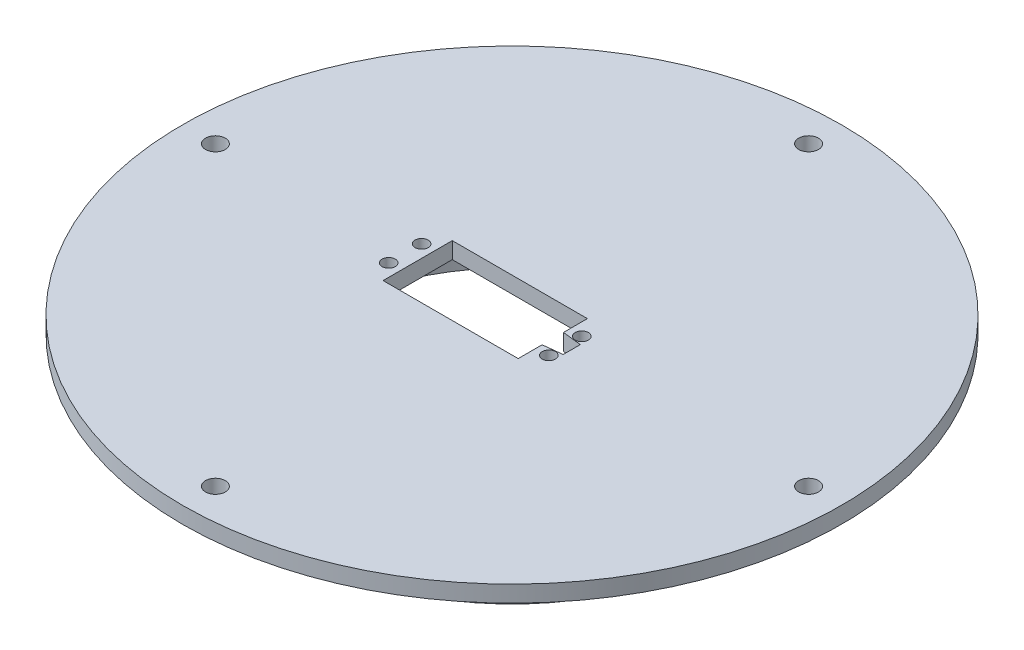
SolidWorks part; units mm, degrees
ref_plane "前视基准面" through (0, 0, 0) normal (0, 0, 1) x (1, 0, 0)
ref_plane "上视基准面" through (0, 0, 0) normal (0, 1, 0) x (1, 0, 0)
ref_plane "右视基准面" through (0, 0, 0) normal (1, 0, 0) x (0, 0, -1)
other "Configuration Table"
sketch "草图1" plane through (0, 0, 0) normal (0, 1, 0) x (1, 0, 0)
  line L0 (0, 0) -> (83.2464, 0) construction
  line L2 (-36.85, 10) -> (-36.85, -10) construction
  line L4 (17.15, 10) -> (17.15, -10) construction
  line L5 (-8.123, 10.2) -> (-8.123, -9.8) construction
  line L7 (-28.623, 10.5) -> (-28.623, -10.5)
  line L8 (-28.623, 10.5) -> (12.377, 10.5)
  line L9 (-28.623, -10.5) -> (12.377, -10.5)
  line L10 (12.377, 10.5) -> (12.377, -10.5)
  circle A0 centre (0, 0) radius 100
  dimension "D1" = 54
  dimension "D4" = 41
  dimension "D8" = 200
  dimension "D2" = 20
  dimension "D3" = 17.15
  dimension "D5" = 10.5
sketch "草图2" plane through (0, 0, 0) normal (0, 1, 0) x (1, 0, 0)
  line L2 (12.377, 10.5) -> (12.377, -10.5) construction
  line L4 (-28.623, 10.5) -> (-28.623, -10.5) construction
  line L5 (12.377, -10.5) -> (-28.623, -10.5)
  line L6 (-8.123, 10.5) -> (-8.123, -10.5) construction
  line L7 (12.377, 10.5) -> (12.377, -10.5)
  line L8 (-28.623, 10.5) -> (12.377, 10.5)
  line L9 (-28.623, 10.5) -> (-28.623, -10.5)
  line L10 (-28.623, 0) -> (12.377, 0) construction
  circle A0 centre (16.177, 5) radius 2
  circle A1 centre (16.177, -5) radius 2
  circle A2 centre (-32.423, -5) radius 2
  circle A3 centre (-32.423, 5) radius 2
  dimension "D2" = 10
  dimension "D1" = 10.5
  dimension "D3" = 48.6
extrude "凸台-拉伸1" add sketch "草图1" along normal blind 5 contours A0
sketch "草图3" plane through (0, 0, 0) normal (0, -1, 0) x (1, 0, 0)
  line L0 (0, 0) -> (0, 109.0175) construction
  circle A0 centre (0, 0) radius 90 construction
  circle A1 centre (0, 90) radius 3
  circle A2 centre (90, 0) radius 3
  circle A3 centre (0, -90) radius 3
  circle A4 centre (-90, 0) radius 3
  dimension "D1" = 4
extrude "切除-拉伸1" cut sketch "草图3" against normal through all
extrude "切除-拉伸3" cut sketch "草图2" along normal blind 10
sketch "草图4" plane through (0, 0, 0) normal (0, -1, 0) x (1, 0, 0)
  circle A0 centre (0, 0) radius 60
  circle A1 centre (0, 0) radius 65
extrude "凸台-拉伸2" add sketch "草图4" along normal blind 25
sketch "草图5" plane through (0, 5, 0) normal (0, 1, 0) x (1, 0, 0)
  line L0 (-28.623, 0) -> (12.377, 0) construction
  line L1 (-28.623, -10.5) -> (-28.623, 10.5) construction
  line L2 (12.377, 10.5) -> (12.377, -10.5) construction
  line L5 (12.377, -3.25) -> (12.377, 3.25)
  line L7 (12.377, 3.25) -> (18.1292, 2.6)
  line L8 (18.1292, 2.6) -> (18.1292, -2.6)
  line L9 (18.1292, 0) -> (12.377, 0)
  line L10 (12.377, -3.25) -> (18.1292, -2.6)
  line M12 (12.377, 10.5) -> (12.377, -10.5)
extrude "切除-拉伸4" cut sketch "草图5" against normal through all contours L9 L8 L7 M12 | L5 L10 L8 L9
sketch "草图6" plane through (-28.623, 0, 0) normal (1, 0, 0) x (0, 0, -1)
  line L0 (0, 0) -> (0, -25) construction
  line L1 (-65, -25) -> (65, -25) construction
  line L2 (5, -25) -> (-5, -25)
  line L3 (-5, -25) -> (-5, -19)
  line L4 (-5, -19) -> (5, -19)
  line L5 (5, -25) -> (5, -19)
  point P10 (0, -19)
  dimension "D1" = 10
  dimension "D2" = 6
extrude "切除-拉伸5" cut sketch "草图6" along normal through all
